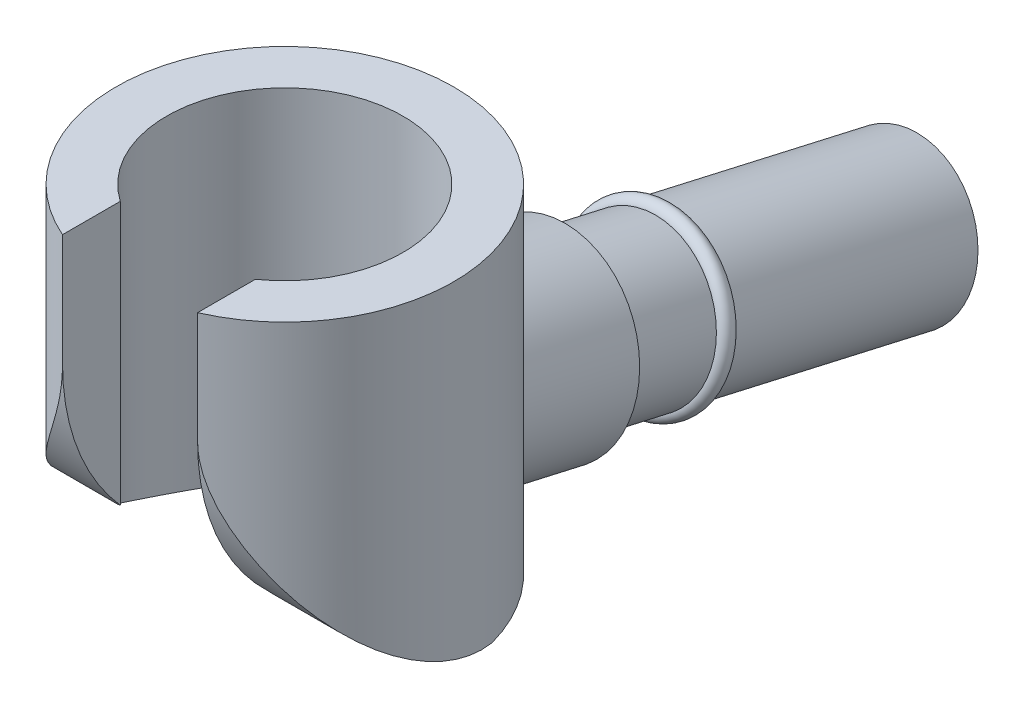
SolidWorks part; units mm, degrees
ref_plane "Front Plane" through (0, 0, 0) normal (0, 0, 1) x (1, 0, 0)
ref_plane "Top Plane" through (0, 0, 0) normal (0, 1, 0) x (1, 0, 0)
ref_plane "Right Plane" through (0, 0, 0) normal (1, 0, 0) x (0, 0, -1)
sketch "Sketch3" plane through (0, 0, 0) normal (0, 1, 0) x (1, 0, 0)
  line L0 (0, 0) -> (0, -1.4179) construction
  line L1 (-1, -1.4361) -> (-1, -2.2913)
  line L2 (1, -1.4361) -> (1, -2.2913)
  arc A0 (1, -2.2913) -> (-1, -2.2913) centre (0, 0) ccw
  arc A1 (1, -1.4361) -> (-1, -1.4361) centre (0, 0) ccw
  dimension "D1" = 5
  dimension "D2" = 3.5
  dimension "D3" = 2
extrude "Boss-Extrude1" add sketch "Sketch3" along normal mid plane 5
sketch "Sketch4" plane through (0, 0, 0) normal (1, 0, 0) x (0, 0, -1)
  line L0 (-2.2913, -2.5) -> (2.5, -2.5) construction
  line L2 (-2.2913, 2.5) -> (-2.2913, -2.5) construction
  line L3 (-2.2913, 0.85) -> (-2.2913, -2.5)
  line L4 (-2.2913, -2.5) -> (0.66, -2.5)
  arc A0 (-2.2913, 0.85) -> (0.66, -2.5) centre (1.0856, 0.85) ccw
  point P1 (0, 0)
  point P2 (-2.2913, -2.3327)
  point P3 (-2.2913, -2.5241)
  point P4 (-2.2913, -2.4762)
  point P5 (0, 0)
  point P6 (0.66, -2.5)
  point P13 (-2.2913, -2.5)
  point P15 (0, 0)
  point P16 (0, 0)
  dimension "D1" = 1.65
  dimension "D2" = 1.84
extrude "Cut-Extrude8" cut sketch "Sketch4" against normal through all both and the other way through all contours A0 L3 L4
sketch "Sketch5" plane through (0, 0, 0) normal (1, 0, 0) x (0, 0, -1)
  line L0 (2.5, -1.11) -> (9.11, -2.6166) construction
  line L1 (2.5, -2.5) -> (2.5, 2.5) construction
  circle A0 centre (5.11, -2.8536) radius 0.125
  dimension "D4" = 0.25
  dimension "D6" = 1.12
  dimension "D1" = 77.16
  dimension "D2" = 6.61
  dimension "D3" = 1.39
  dimension "D5" = 4
ref_plane "Plane1" through (0, -2.6166, -9.11) normal (0, -0.2222, -0.975) x (-1, 0, 0)
sketch "Sketch6" plane through (0, -2.6166, -9.11) normal (0, -0.2222, -0.975) x (-1, 0, 0)
  circle A0 centre (0, 0) radius 1.125
  dimension "D1" = 2.25
extrude "Boss-Extrude2" add sketch "Sketch6" against normal up to surface (7.0359 mm away)
sketch "Sketch7" plane through (0, -2.6166, -9.11) normal (0, -0.2222, -0.975) x (-1, 0, 0)
  circle A0 centre (0, 0) radius 1.375
  dimension "D1" = 2.75
extrude "Boss-Extrude4" add sketch "Sketch7" against normal up to body from offset 5.4 separate body offset against normal yes
revolve "Revolve1" add sketch "Sketch5" angle 360 about L0
